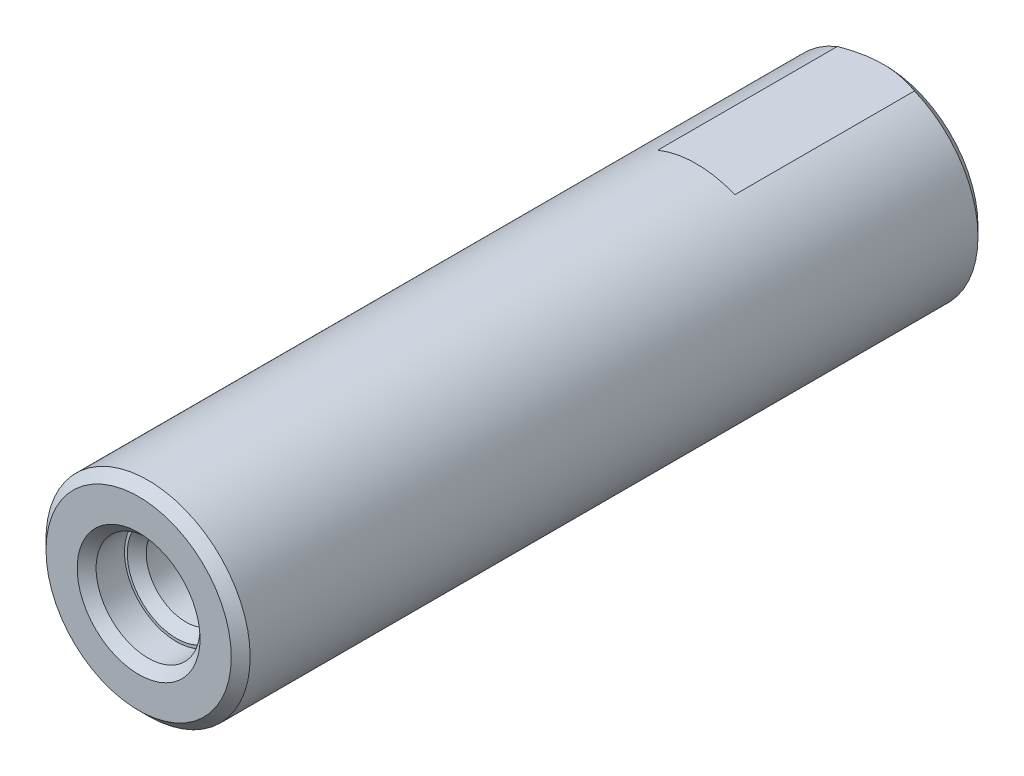
SolidWorks part; units mm, degrees
material "2A12"
ref_plane "前视基准面" through (0, 0, 0) normal (0, 0, 1) x (1, 0, 0)
ref_plane "上视基准面" through (0, 0, 0) normal (0, 1, 0) x (1, 0, 0)
ref_plane "右视基准面" through (0, 0, 0) normal (1, 0, 0) x (0, 0, -1)
sketch "草图1" plane through (0, 0, 0) normal (0, 0, 1) x (1, 0, 0)
  circle A0 centre (0, 0) radius 5.4
  dimension "D1" = 10.8
extrude "拉伸1" add sketch "草图1" along normal blind 39.5
hole_wizard "M5 螺纹孔2" positions "3D草图1" profile "草图5" tap size "M5" standard "GB"
sketch3d "3D草图1"
  line L0 (0, 0, 39.5) -> (0, 0, 0) construction
  point P0 (0, 0, 39.5)
sketch "草图5" plane through (0, 0, 39.5) normal (1, 0, 0) x (0, -1, 0)
  line L0 (0, 0) -> (0, 13.6618)
  line L1 (0, 13.6618) -> (2.1, 12.4)
  line L2 (2.1, 12.4) -> (2.1, 0)
  line L5 (2.1, 0) -> (0, 0)
  line L10 (0, 13.6618) -> (-2.1, 12.4) construction
  line L11 (0, -6.35) -> (0, 107.95) construction
  dimension "螺纹孔钻头直径" = 4.2
  dimension "螺纹孔钻头深度" = 12.4
  dimension "导头角度" = 118
cosmetic thread "孔螺蚊线1" parameters "D1"=8, "D2"=5
chamfer "倒角2" distance 0.5 angle 45 1 edges at (5.4, 0, 39.5)
sketch "草图9" plane through (0, 0, 39.5) normal (0, 0, 1) x (1, 0, 0)
  circle A0 centre (0, 0) radius 2.75
  dimension "D1" = 5.5
extrude "拉伸5" cut sketch "草图9" against normal blind 2
chamfer "倒角3" distance 0.5 angle 45 2 edges at (2.75, 0, 39.5) (2.1, 0, 37.5)
chamfer "倒角4" distance 0.5 angle 45 1 edges at (5.4, 0, 0)
hole_wizard "M5 螺纹孔1" positions "3D草图2" profile "草图10" tap size "M5" standard "GB"
sketch3d "3D草图2"
  point P0 (0, 0, 0)
sketch "草图10" plane through (0, 0, 0) normal (1, 0, 0) x (0, 1, 0)
  line L0 (0, 0) -> (0, 13.6618)
  line L1 (0, 13.6618) -> (2.1, 12.4)
  line L2 (2.1, 12.4) -> (2.1, 0)
  line L5 (2.1, 0) -> (0, 0)
  line L10 (0, 13.6618) -> (-2.1, 12.4) construction
  line L11 (0, -6.35) -> (0, 107.95) construction
  dimension "螺纹孔钻头直径" = 4.2
  dimension "螺纹孔钻头深度" = 12.4
  dimension "导头角度" = 118
cosmetic thread "孔螺蚊线2" parameters "D1"=10, "D2"=5
chamfer "倒角5" distance 0.5 angle 45 1 edges at (-2.1, 0, 0)
sketch "草图11" plane through (0, 0, 0) normal (0, 0, 1) x (1, 0, 0)
  line L0 (0, 0) -> (0, 5) construction
  line L1 (-5, 7) -> (5, 7)
  line L2 (-5, 7) -> (-5, 5)
  line L3 (-5, 5) -> (5, 5)
  line L4 (5, 7) -> (5, 5)
  dimension "D1" = 5
  dimension "D2" = 2
  dimension "D3" = 10
extrude "拉伸6" cut sketch "草图11" along normal blind 10
mirror "镜向1" about plane through (0, 0, 0) normal (0, 1, 0) of "拉伸6"
